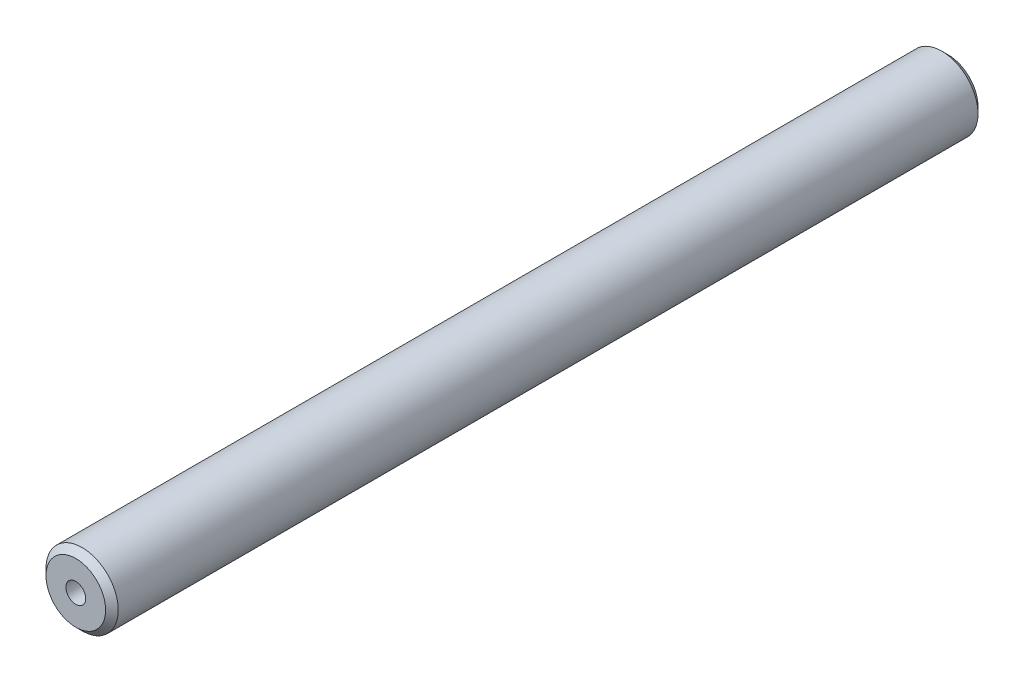
SolidWorks part; units mm, degrees
ref_plane "Ön Düzlem" through (0, 0, 0) normal (0, 0, 1) x (1, 0, 0)
ref_plane "Üst Düzlem" through (0, 0, 0) normal (0, 1, 0) x (1, 0, 0)
ref_plane "Sağ Düzlem" through (0, 0, 0) normal (1, 0, 0) x (0, 0, -1)
sketch "Çizim1" plane through (0, 0, 0) normal (0, 0, 1) x (1, 0, 0)
  circle A0 centre (0, 0) radius 4
  dimension "D1" = 8
extrude "Yükseklik-Ekstrüzyon1" add sketch "Çizim1" along normal blind 96.6
sketch "Çizim3" plane through (0, 0, 96.6) normal (0, 0, 1) x (1, 0, 0)
  circle A0 centre (0, 0) radius 1.1
  dimension "D1" = 2.2
extrude "Kes-Ekstrüzyon2" cut sketch "Çizim3" against normal blind 25
chamfer "Pah1" distance 0.7 angle 45 1 edges at (4, 0, 96.6)
chamfer "Pah2" distance 0.7 angle 45 1 edges at (4, 0, 0)
